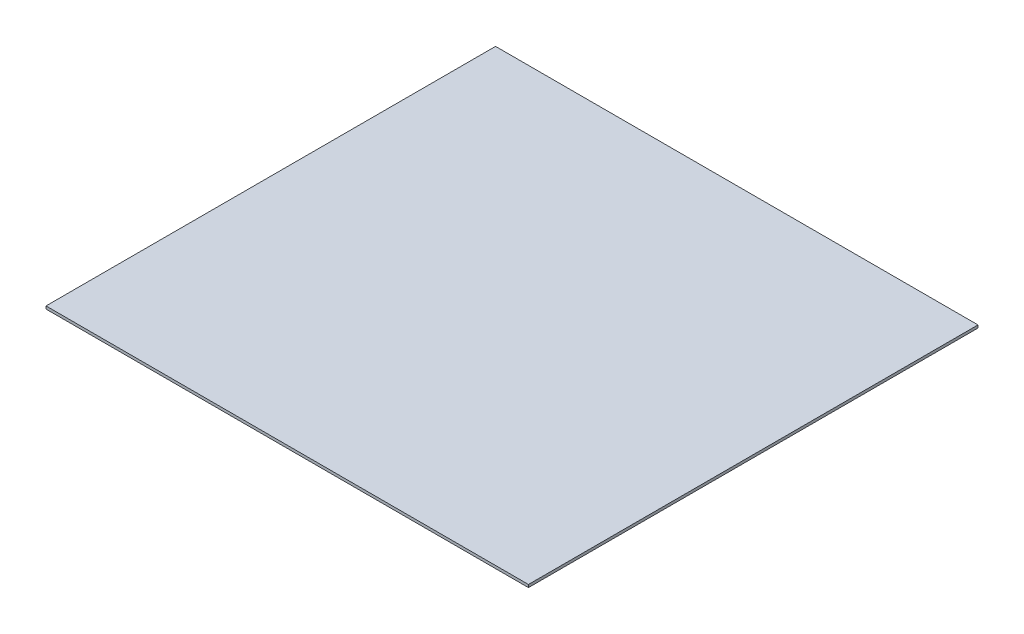
SolidWorks part; units mm, degrees
ref_plane "Front Plane" through (0, 0, 0) normal (0, 0, 1) x (1, 0, 0)
ref_plane "Top Plane" through (0, 0, 0) normal (0, 1, 0) x (1, 0, 0)
ref_plane "Right Plane" through (0, 0, 0) normal (1, 0, 0) x (0, 0, -1)
sketch "Sketch1" plane through (0, 0, 0) normal (0, 1, 0) x (1, 0, 0)
  line L1 (0, 0) -> (13411.2, 0)
  line L2 (0, 0) -> (0, 12496.8)
  line L3 (0, 12496.8) -> (13411.2, 12496.8)
  line L4 (13411.2, 0) -> (13411.2, 12496.8)
  dimension "D1" = 13411.2
  dimension "D2" = 12496.8
extrude "Boss-Extrude1" add sketch "Sketch1" along normal blind 76.2
